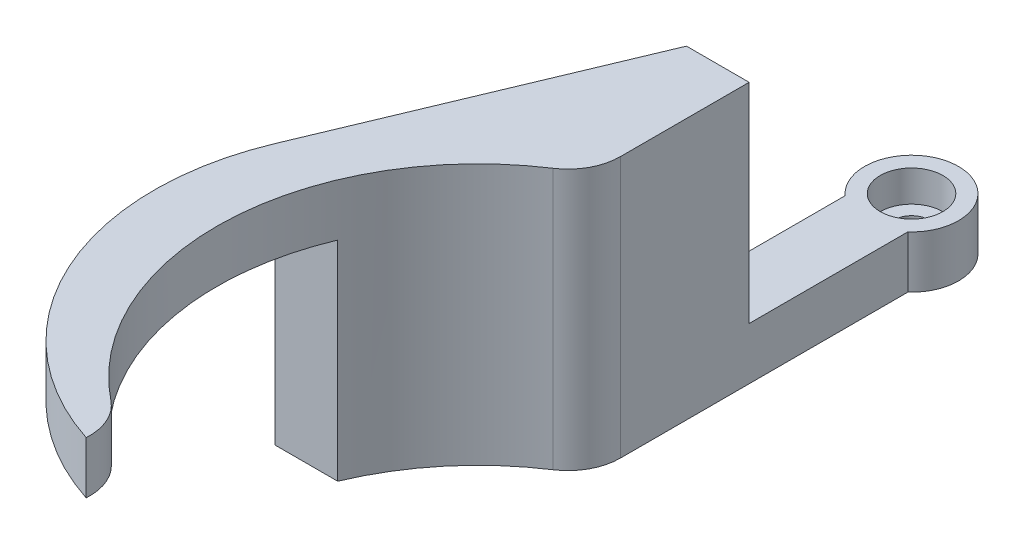
SolidWorks part; units mm, degrees
ref_plane "前视基准面" through (0, 0, 0) normal (0, 0, 1) x (1, 0, 0)
ref_plane "上视基准面" through (0, 0, 0) normal (0, 1, 0) x (1, 0, 0)
ref_plane "右视基准面" through (0, 0, 0) normal (1, 0, 0) x (0, 0, -1)
other "Configuration Table"
sketch "草图3" plane through (0, 0, 0) normal (0, 1, 0) x (1, 0, 0)
  line L0 (0, 0) -> (0, -9.9636) construction
  line L1 (-3, -3.3541) -> (3, -3.3541) construction
  line L2 (-3, -3.3541) -> (-3, -7.4162)
  line L3 (3, -3.3541) -> (3, -7.4162)
  line L7 (3, -7.4162) -> (3, -10.583)
  line L10 (-3, -43.8541) -> (3, -43.8541)
  line L11 (3, -43.8541) -> (3, -10.583)
  line L13 (-3, -7.4162) -> (-3, -43.8541)
  arc A0 (3, -3.3541) -> (-3, -3.3541) centre (0, 0) ccw
  point P6 (0, -3.3541)
  dimension "D1" = 9
  dimension "D2" = 6
  dimension "16.66" = 40.5
extrude "凸台-拉伸2" add sketch "草图3" along normal blind 5
sketch "草图4" plane through (0, 5, 0) normal (0, 1, 0) x (1, 0, 0)
  circle A0 centre (0, 0) radius 1.65
  dimension "D1" = 3.3
extrude "切除-拉伸1" cut sketch "草图4" against normal up to surface (5 mm away) up to face at (0, 0, 21.6406)
sketch "草图6" plane through (0, 5, 0) normal (0, 1, 0) x (1, 0, 0)
  line L0 (14.4495, -55.9701) -> (14.4495, -20.0301) construction
  line L1 (14.4495, -55.9701) -> (3, -43.8541) construction
  line L2 (3, -68.0861) -> (0.6636, -72.1328) construction
  line L3 (3, -43.8541) -> (-3, -43.8541) construction
  line L4 (3, -33.746) -> (-3, -33.746)
  line L5 (3, -43.8541) -> (3, -3.3541) construction
  line L6 (-3, -3.3541) -> (-3, -43.8541) construction
  line L7 (14.4495, -55.9701) -> (1.9495, -77.6207) construction
  line L8 (1.9495, -77.6207) -> (0.7225, -79.746)
  arc A0 (3, -43.8541) -> (3, -68.0861) centre (14.4495, -55.9701) ccw construction
  arc A1 (-3, -43.8541) -> (0.6636, -72.1328) centre (14.4495, -55.9701) ccw construction
  arc A4 (-3, -33.746) -> (0.7225, -79.746) centre (8.4495, -55.9701) ccw
  arc A5 (3, -33.746) -> (1.9495, -77.6207) centre (14.4495, -55.9701) ccw
  dimension "D1" = 33.34
  dimension "D3" = 30
  dimension "D4" = 30
  dimension "D2" = 43.38
extrude "凸台-拉伸3" add sketch "草图6" against normal blind 5
sketch "草图7" plane through (0, 5, 0) normal (0, 1, 0) x (1, 0, 0)
  circle A0 centre (0, 0) radius 3
  dimension "D1" = 6
extrude "切除-拉伸2" cut sketch "草图7" against normal blind 3
sketch "草图8" plane through (0, 5, 0) normal (0, 1, 0) x (1, 0, 0)
  line L0 (-3, -38.0672) -> (-3, -43.8541)
  line L1 (-3, -43.8541) -> (3, -43.8541)
  line L2 (3, -43.8541) -> (3, -33.746)
  line L3 (3, -43.8541) -> (3, -3.3541) construction
  arc A0 (3, -33.746) -> (-3, -38.0672) centre (14.4495, -55.9701) ccw
extrude "切除-拉伸3" cut sketch "草图8" against normal blind 7.5
sketch "草图9" plane through (0, 5, 0) normal (0, 1, 0) x (1, 0, 0)
  line L0 (-3, -18.5501) -> (-14.615, -46.3249)
  line L1 (-3, -3.3541) -> (-3, -33.746) construction
  line L2 (-3, -33.746) -> (-3, -18.5501)
  arc A0 (-3, -33.746) -> (0.7225, -79.746) centre (8.4495, -55.9701) ccw construction
  arc A1 (-3, -33.746) -> (-14.615, -46.3249) centre (8.4495, -55.9701) ccw
extrude "凸台-拉伸4" add sketch "草图9" against normal blind 5
fillet "圆角1" radius 5 2 edges at (1.9495, 2.5, 77.6207) (3, 2.5, 33.746)
sketch "草图10" plane through (0, 5, 0) normal (0, 1, 0) x (1, 0, 0)
  line L0 (-3, -18.5501) -> (3, -18.5501)
  line L1 (-14.615, -46.3249) -> (-8.615, -46.3249)
  line L3 (3, -30.882) -> (3, -3.3541)
  line L4 (-3, -3.3541) -> (-3, -18.5501)
  line L5 (-3, -18.5501) -> (-14.615, -46.3249)
  line L6 (3, -30.882) -> (3, -18.5501)
  line L8 (-3, -18.5501) -> (-14.615, -46.3249)
  arc A5 (-14.615, -46.3249) -> (0.7225, -79.746) centre (8.4495, -55.9701) ccw
  arc A6 (0.7225, -79.746) -> (-1.1472, -75.5083) centre (-4.2666, -79.4159) ccw
  arc A7 (0.7416, -35.0633) -> (-1.1472, -75.5083) centre (14.4495, -55.9701) ccw
  arc A8 (0.7416, -35.0633) -> (3, -30.882) centre (-2, -30.882) ccw
  arc A9 (3, -3.3541) -> (-3, -3.3541) centre (0, 0) ccw
  arc A11 (0.7225, -79.746) -> (-1.1472, -75.5083) centre (-4.2666, -79.4159) ccw
  arc A12 (0.7416, -35.0633) -> (-8.615, -46.3249) centre (14.4495, -55.9701) ccw
  arc A13 (0.7416, -35.0633) -> (3, -30.882) centre (-2, -30.882) ccw
  arc M11 (-1.1472, -75.5083) -> (0.7416, -35.0633) centre (14.4495, -55.9701) cw
  arc M12 (0.7416, -35.0633) -> (3, -30.882) centre (-2, -30.882) ccw
  line M13 (3, -30.882) -> (3, -3.3541)
  line M16 (-3, -18.5501) -> (-14.615, -46.3249)
  dimension "D1" = 0
extrude "凸台-拉伸5" add sketch "草图10" along normal blind 15 contours L1 L0 M16 M11 M12 M13
sketch "草图11" plane through (0, 20, 0) normal (0, 1, 0) x (1, 0, 0)
  line L1 (-8.615, -46.3249) -> (-14.615, -46.3249)
  line L4 (-3, -18.5501) -> (-14.615, -46.3249)
  line L5 (-14.615, -46.3249) -> (-8.615, -46.3249)
  line L6 (3, -30.882) -> (3, -18.5501)
  line L7 (3, -18.5501) -> (-3, -18.5501)
  line L8 (-3, -18.5501) -> (-14.615, -46.3249)
  line L10 (3, -30.882) -> (3, -18.5501)
  line L11 (3, -18.5501) -> (-3, -18.5501)
  arc A2 (0.7416, -35.0633) -> (-8.615, -46.3249) centre (14.4495, -55.9701) ccw
  arc A3 (0.7416, -35.0633) -> (3, -30.882) centre (-2, -30.882) ccw
  arc A4 (0.7416, -35.0633) -> (-8.615, -46.3249) centre (14.4495, -55.9701) ccw
  arc A5 (0.7416, -35.0633) -> (3, -30.882) centre (-2, -30.882) ccw
  arc A7 (-14.615, -46.3249) -> (0.7225, -79.746) centre (8.4495, -55.9701) ccw
  arc A8 (0.7225, -79.746) -> (-1.1472, -75.5083) centre (-4.2666, -79.4159) ccw
  arc A9 (-8.615, -46.3249) -> (-1.1472, -75.5083) centre (14.4495, -55.9701) ccw
  arc A10 (-14.615, -46.3249) -> (0.7225, -79.746) centre (8.4495, -55.9701) ccw
  arc A11 (0.7225, -79.746) -> (-1.1472, -75.5083) centre (-4.2666, -79.4159) ccw
  arc A12 (-8.615, -46.3249) -> (-1.1472, -75.5083) centre (14.4495, -55.9701) ccw
  dimension "D1" = 0
  dimension "D2" = 0
extrude "凸台-拉伸6" add sketch "草图11" along normal blind 5
sketch "草图12" plane through (0, 5, 0) normal (0, 1, 0) x (1, 0, 0)
  line L1 (-8.615, -46.3249) -> (-14.615, -46.3249)
  line L2 (-8.615, -46.3249) -> (-14.615, -46.3249)
  arc A3 (-14.615, -46.3249) -> (0.7225, -79.746) centre (8.4495, -55.9701) ccw
  arc A4 (0.7225, -79.746) -> (-1.1472, -75.5083) centre (-4.2666, -79.4159) ccw
  arc A5 (-8.615, -46.3249) -> (-1.1472, -75.5083) centre (14.4495, -55.9701) ccw
  arc A6 (-14.615, -46.3249) -> (0.7225, -79.746) centre (8.4495, -55.9701) ccw
  arc A7 (0.7225, -79.746) -> (-1.1472, -75.5083) centre (-4.2666, -79.4159) ccw
  arc A8 (-8.615, -46.3249) -> (-1.1472, -75.5083) centre (14.4495, -55.9701) ccw
  dimension "D1" = 0
extrude "切除-拉伸4" cut sketch "草图12" against normal blind 5
